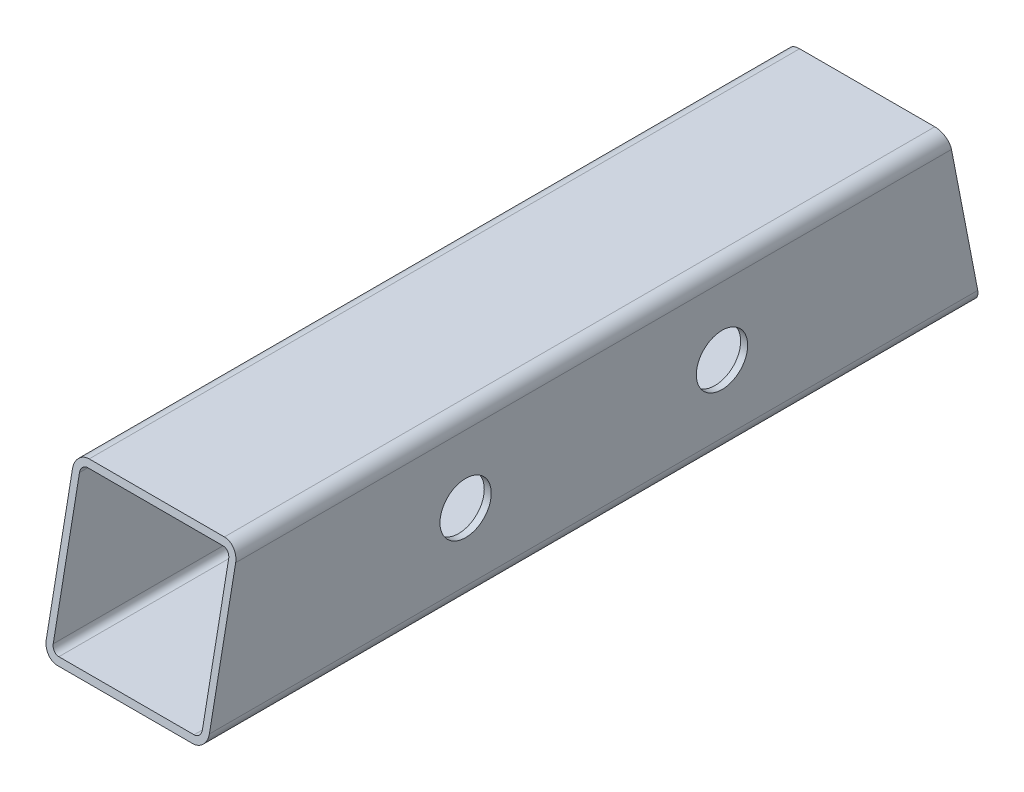
SolidWorks part; units mm, degrees
material "ASTM A36 Steel"
ref_plane "Front Plane" through (0, 0, 0) normal (0, 0, 1) x (1, 0, 0)
ref_plane "Top Plane" through (0, 0, 0) normal (0, 1, 0) x (1, 0, 0)
ref_plane "Right Plane" through (0, 0, 0) normal (1, 0, 0) x (0, 0, -1)
sketch "Sketch1" plane through (0, 0, 0) normal (0, 0, 1) x (1, 0, 0)
  line L1 (22.4793, 29.5118) -> (-35.5207, 29.5118)
  line L2 (28.4793, 23.5118) -> (28.4793, -34.4882)
  line L3 (22.4793, -40.4882) -> (-35.5207, -40.4882)
  line L4 (-41.5207, 23.5118) -> (-41.5207, -34.4882)
  line L5 (22.4793, 26.5118) -> (-35.5207, 26.5118)
  line L6 (25.4793, 23.5118) -> (25.4793, -34.4882)
  line L7 (22.4793, -37.4882) -> (-35.5207, -37.4882)
  line L8 (-38.5207, 23.5118) -> (-38.5207, -34.4882)
  arc A0 (22.4793, 29.5118) -> (28.4793, 23.5118) centre (22.4793, 23.5118) cw
  arc A1 (28.4793, -34.4882) -> (22.4793, -40.4882) centre (22.4793, -34.4882) cw
  arc A2 (-35.5207, -40.4882) -> (-41.5207, -34.4882) centre (-35.5207, -34.4882) cw
  arc A3 (-41.5207, 23.5118) -> (-35.5207, 29.5118) centre (-35.5207, 23.5118) cw
  arc A4 (22.4793, 26.5118) -> (25.4793, 23.5118) centre (22.4793, 23.5118) cw
  arc A5 (25.4793, -34.4882) -> (22.4793, -37.4882) centre (22.4793, -34.4882) cw
  arc A6 (-35.5207, -37.4882) -> (-38.5207, -34.4882) centre (-35.5207, -34.4882) cw
  arc A7 (-38.5207, 23.5118) -> (-35.5207, 26.5118) centre (-35.5207, 23.5118) cw
  point P10 (28.4793, 29.5118)
  point P15 (-41.5207, -40.4882)
  point P18 (-41.5207, 29.5118)
  point P23 (25.4793, -37.4882)
  point P26 (-38.5207, -37.4882)
  point P29 (-38.5207, 26.5118)
  dimension "D7" = 6
  dimension "D8" = 3
  dimension "D1" = 70
  dimension "D2" = 70
  dimension "D3" = 64
  dimension "D4" = 64
  dimension "D5" = 3
  dimension "D6" = 3
extrude "Boss-Extrude1" add sketch "Sketch1" along normal blind 332
sketch "Sketch2" plane through (28.4793, 0, 0) normal (1, 0, 0) x (0, 0, -1)
  line L0 (0, -40.4882) -> (-13.6, 29.5118)
  line L1 (-332, 29.5118) -> (0, 29.5118) construction
  line L2 (-13.6, 29.5118) -> (0, 29.5118)
  line L3 (0, 29.5118) -> (0, -40.4882)
  line L4 (-332, -40.4882) -> (-332, 29.5118)
  line L6 (-332, 29.5118) -> (-318.4, 29.5118)
  line L7 (-318.4, 29.5118) -> (-332, -40.4882)
  line L8 (-332, -40.4882) -> (-329.5637, -41.4425)
  line L9 (-332, -40.4882) -> (0, -40.4882) construction
  circle A0 centre (-220.9, -5.4882) radius 7.5
  circle A1 centre (-110.9, -5.4882) radius 7.5
  line M3 (0, -34.4882) -> (0, 23.5118)
  line M4 (0, 23.5118) -> (-332, 23.5118)
  line M5 (-332, 23.5118) -> (-332, -34.4882)
  line M6 (-332, -34.4882) -> (0, -34.4882)
  dimension "D5" = 15
  dimension "D6" = 15
  dimension "D1" = 13.6
  dimension "D2" = 13.6
  dimension "D3" = 97.5
  dimension "D4" = 110
  dimension "D7" = 35
  dimension "D8" = 35
  dimension "D9" = 304.8
extrude "Cut-Extrude1" cut sketch "Sketch2" against normal blind 330 contours L7 M4 M5 M6 | A0 | L3 L2 L0 M4 | L0 M6 M3 M4 | A1
sketch "Sketch3" plane through (28.4793, 0, 0) normal (1, 0, 0) x (0, 0, -1)
  circle A0 centre (-220.9, -5.4882) radius 11
  circle A1 centre (-110.9, -5.4882) radius 11
  dimension "D1" = 22
  dimension "D2" = 22
extrude "Cut-Extrude2" cut sketch "Sketch3" against normal blind 5
